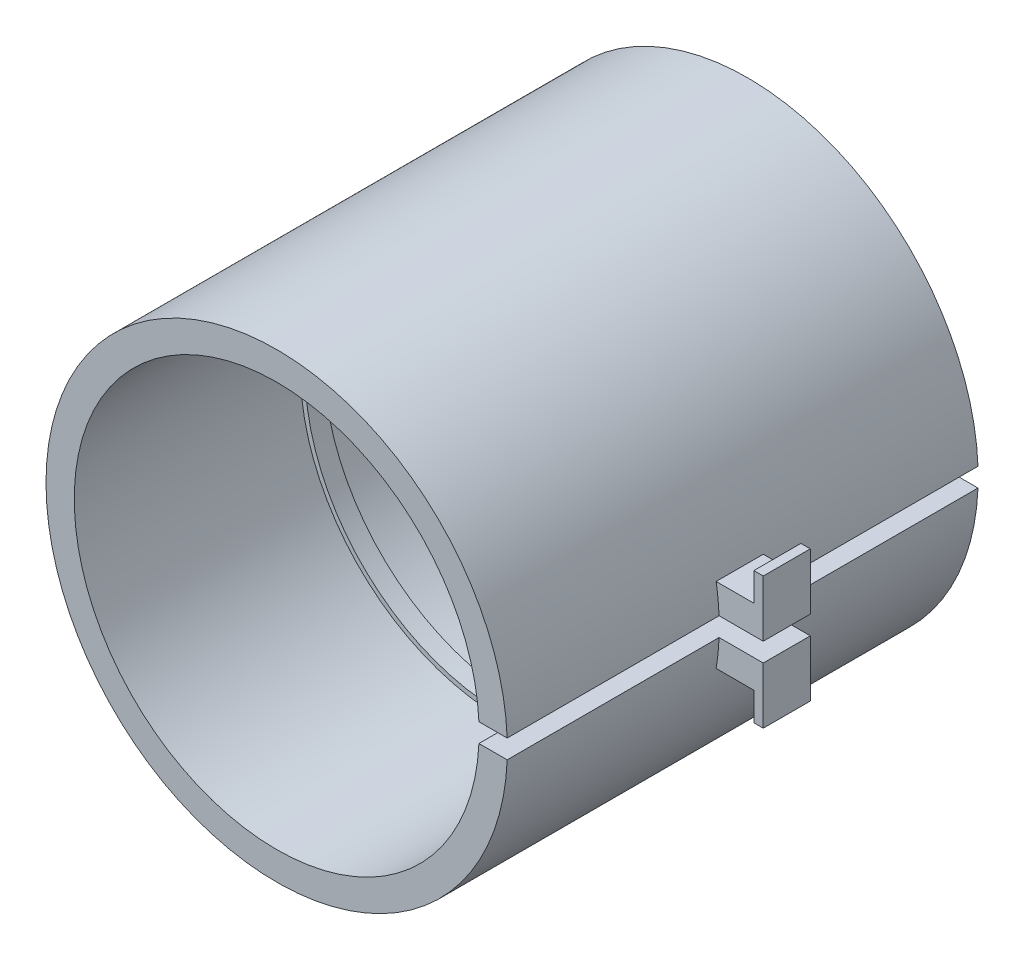
SolidWorks part; units mm, degrees
ref_plane "Front Plane" through (0, 0, 0) normal (0, 0, 1) x (1, 0, 0)
ref_plane "Top Plane" through (0, 0, 0) normal (0, 1, 0) x (1, 0, 0)
ref_plane "Right Plane" through (0, 0, 0) normal (1, 0, 0) x (0, 0, -1)
sketch "Sketch1" plane through (0, 0, 0) normal (0, 0, 1) x (1, 0, 0)
  line L0 (21.4767, 1) -> (21.4767, -1) construction
  line L1 (21.4767, 1) -> (24.4796, 1)
  line L2 (21.4767, -1) -> (24.4796, -1)
  circle A0 centre (0, 0) radius 21.5 construction
  circle A1 centre (0, 0) radius 24.5 construction
  arc A2 (21.4767, 1) -> (21.4767, -1) centre (0, 0) ccw
  arc A3 (24.4796, 1) -> (24.4796, -1) centre (0, 0) ccw
  dimension "D1" = 43
  dimension "D3" = 2
  dimension "D2" = 3
extrude "Boss-Extrude1" add sketch "Sketch1" along normal blind 50
ref_plane "Plane1" through (0, 0, 25) normal (0, 0, 1) x (1, 0, 0)
sketch "Sketch2" plane through (0, 0, 25) normal (0, 0, 1) x (1, 0, 0)
  line L0 (24.4796, 1) -> (29.1713, 1)
  line L1 (29.1713, 1) -> (29.1713, 4)
  line L2 (29.1713, 4) -> (24.1713, 4)
  line L3 (0, 0) -> (50000, 0) construction
  line L4 (29.1713, -4) -> (24.1713, -4)
  line L5 (29.1713, -1) -> (29.1713, -4)
  line L6 (24.4796, -1) -> (29.1713, -1)
  arc A0 (24.4796, 1) -> (24.4796, -1) centre (0, 0) ccw construction
  arc A1 (24.1713, 4) -> (24.4796, 1) centre (0, 0) cw
  arc A2 (24.1713, -4) -> (24.4796, -1) centre (0, 0) ccw
  dimension "D1" = 3
  dimension "D2" = 5
extrude "Boss-Extrude2" add sketch "Sketch2" along normal mid plane 5
sketch "Sketch3" plane through (0, 0, 25) normal (0, 0, 1) x (1, 0, 0)
  line L0 (21.4767, 1) -> (20.9762, 1)
  line L1 (21.4767, -1) -> (20.9762, -1)
  circle A0 centre (0, 0) radius 21.5
  circle A1 centre (0, 0) radius 21
  point P9 (0, 0)
  point P10 (0, 0)
  point P12 (0, 0)
  dimension "D1" = 0.5
extrude "Boss-Extrude3" add sketch "Sketch3" along normal mid plane 2 contours A1 L0 A0 L1
sketch "Sketch4" plane through (0, 4, 0) normal (0, 1, 0) x (1, 0, 0)
  line L0 (29.1713, -22.5) -> (24.1713, -22.5) construction
  line L1 (29.1713, -27.5) -> (28.1713, -27.5)
  line L2 (29.1713, -27.5) -> (29.1713, -22.5)
  line L3 (29.1713, -22.5) -> (28.1713, -22.5)
  line L4 (28.1713, -27.5) -> (28.1713, -22.5)
  line L5 (29.1713, -27.5) -> (28.1713, -22.5) construction
  line L6 (29.1713, -22.5) -> (28.1713, -27.5) construction
  point P4 (28.6713, -25)
  dimension "D1" = 1
extrude "Boss-Extrude4" add sketch "Sketch4" along normal blind 3
ref_plane "Plane2" through (0, 0, 0) normal (0, 1, 0) x (1, 0, 0)
mirror "Mirror1" about plane through (0, 0, 0) normal (0, 1, 0) of "Boss-Extrude4"
